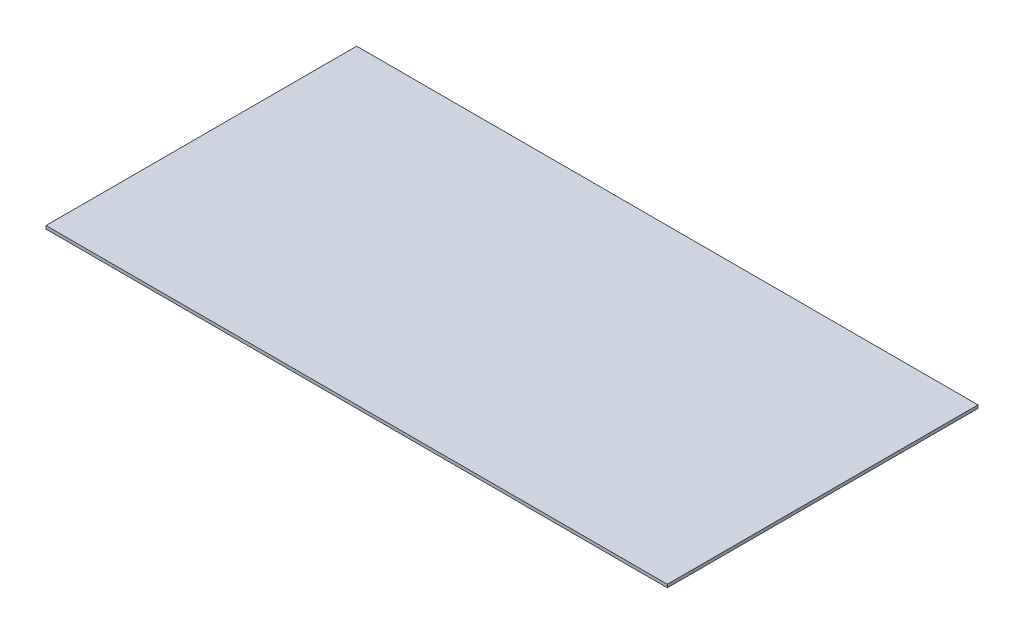
SolidWorks part; units mm, degrees
ref_plane "Front Plane" through (0, 0, 0) normal (0, 0, 1) x (1, 0, 0)
ref_plane "Top Plane" through (0, 0, 0) normal (0, 1, 0) x (1, 0, 0)
ref_plane "Right Plane" through (0, 0, 0) normal (1, 0, 0) x (0, 0, -1)
sketch "Sketch1" plane through (0, 0, 0) normal (0, 1, 0) x (1, 0, 0)
  line L1 (-10000, 5000) -> (10000, 5000)
  line L2 (-10000, 5000) -> (-10000, -5000)
  line L3 (-10000, -5000) -> (10000, -5000)
  line L4 (10000, 5000) -> (10000, -5000)
  line L5 (0, -5000) -> (0, 5000) construction
  line L6 (-10000, 0) -> (10000, 0) construction
  point P4 (0, 0)
  point P5 (0, 0)
  point P260 (0, 0)
  dimension "D1" = 20000
  dimension "D2" = 10000
extrude "Boss-Extrude1" add sketch "Sketch1" along normal blind 100
